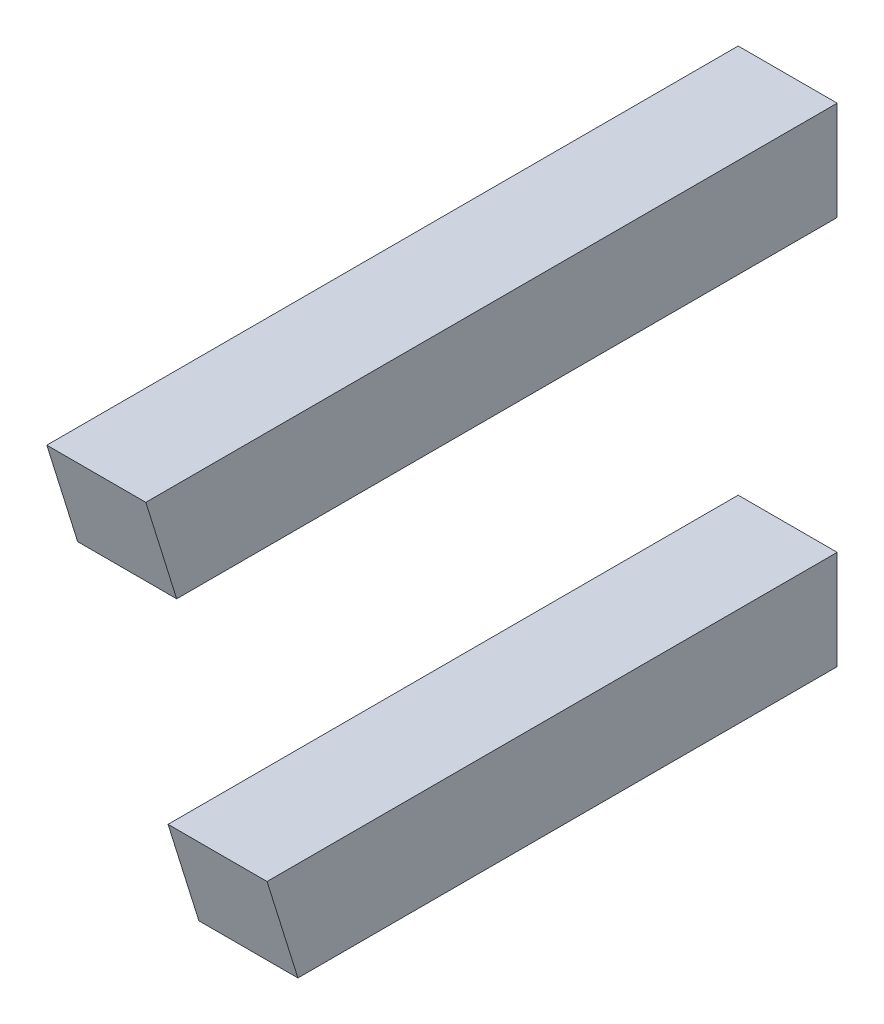
SolidWorks part; units mm, degrees
ref_plane "Front Plane" through (0, 0, 0) normal (0, 0, 1) x (1, 0, 0)
ref_plane "Top Plane" through (0, 0, 0) normal (0, 1, 0) x (1, 0, 0)
ref_plane "Right Plane" through (0, 0, 0) normal (1, 0, 0) x (0, 0, -1)
sketch "Sketch1" plane through (0, 0, 0) normal (0, 0, 1) x (1, 0, 0)
  line L0 (0, 11) -> (2.8, 11)
  line L5 (0, 0) -> (2.8, 0)
  line L6 (0, 0) -> (0, 13.8)
  line L7 (0, 13.8) -> (2.8, 13.8)
  line L8 (2.8, 0) -> (2.8, 13.8)
  line L9 (2.8, 11) -> (2.8, 2.8)
  line L10 (2.8, 2.8) -> (0, 2.8)
  dimension "D1" = 8.2
  dimension "D2" = 2.8
  dimension "D3" = 2.8
  dimension "D4" = 2.8
extrude "Boss-Extrude1" add sketch "Sketch1" against normal blind 20 contours L0 L8 L7 L6 | L8 L10 L6 L5
sketch "Sketch2" plane through (2.8, 0, 0) normal (1, 0, 0) x (0, 0, -1)
  line L0 (20, 0) -> (4.5, 0)
  line L1 (20, 0) -> (0, 0) construction
  line L2 (4.5, 0) -> (-1.7331, 20)
  line L3 (-1.7331, 20) -> (-2.7331, 20)
  line L4 (-2.7331, 20) -> (-2.7331, 0)
  line L5 (-2.7331, 0) -> (4.5, 0)
  line L6 (4.5, 0) -> (5.1233, -2)
  line L7 (5.1233, -2) -> (-2.7331, -2)
  line L8 (-2.7331, -2) -> (-2.7331, 0)
  line L9 (-2.7331, 0) -> (4.5, 0)
  line M6 (0, 2.8) -> (0, 0)
  line M7 (0, 0) -> (20, 0)
  line M9 (20, 2.8) -> (0, 2.8)
  dimension "D1" = 15.5
  dimension "D2" = 107.31
  dimension "D3" = 1
  dimension "D4" = 20
  dimension "D5" = 2
extrude "Cut-Extrude1" cut sketch "Sketch2" against normal through all both and the other way through all contours L4 L5 L2 L3 M6 M9 | L8 L7 L6 L5 M7 | L2 M7 M9 M6
chamfer "Chamfer1" distance 0.25 angle 45 4 edges at (1.4, 2.8, -20) (0, 1.4, -20) (1.4, 0, -20) (2.8, 1.4, -20)
chamfer "Chamfer2" distance 0.25 angle 45 4 edges at (2.8, 12.4, -20) (1.4, 13.8, -20) (0, 12.4, -20) (1.4, 11, -20)
